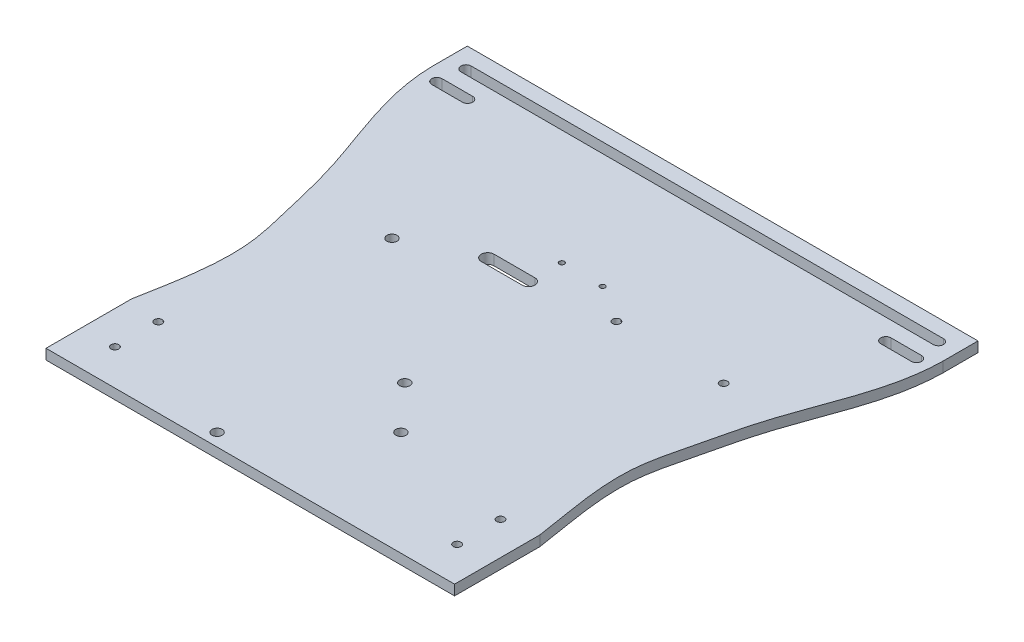
SolidWorks part; units mm, degrees
ref_plane "Front Plane" through (0, 0, 0) normal (0, 0, 1) x (1, 0, 0)
ref_plane "Top Plane" through (0, 0, 0) normal (0, 1, 0) x (1, 0, 0)
ref_plane "Right Plane" through (0, 0, 0) normal (1, 0, 0) x (0, 0, -1)
sketch "Esquisse1" plane through (0, 0, 0) normal (0, 1, 0) x (1, 0, 0)
  line L4 (20.099, -176.7531) -> (180.099, -176.7531)
  line L11 (180.099, -143.3042) -> (180.099, -176.7531)
  line L24 (20.099, -143.3042) -> (20.099, -176.7531)
  line L26 (7.599, 0.2469) -> (192.599, 0.2469) construction
  line L27 (7.599, 2.2469) -> (192.599, 2.2469)
  line L28 (7.599, -1.7531) -> (192.599, -1.7531)
  line L35 (200.099, 8.2469) -> (0.099, 8.2469)
  line L36 (-12.479, 15.7469) -> (206.8188, 15.7469) construction
  line L37 (182, -9.7531) -> (194, -9.7531) construction
  line L38 (182, -7.7531) -> (194, -7.7531)
  line L39 (182, -11.7531) -> (194, -11.7531)
  line L40 (18.198, -9.7531) -> (6.198, -9.7531) construction
  line L41 (18.198, -7.7531) -> (6.198, -7.7531)
  line L42 (18.198, -11.7531) -> (6.198, -11.7531)
  line L45 (0.099, -5.4026) -> (0.099, 8.2469)
  line L46 (75.9115, -59.5989) -> (91.9115, -59.5989) construction
  line L59 (75.9115, -57.0989) -> (91.9115, -57.0989)
  line L60 (75.9115, -62.0989) -> (91.9115, -62.0989)
  line L61 (200.099, -5.4026) -> (200.099, 8.2469)
  circle A1 centre (33.099, -145.7531) radius 1.5
  circle A2 centre (33.099, -162.7531) radius 1.5
  circle A4 centre (167.099, -162.7531) radius 1.5
  circle A5 centre (167.099, -145.7531) radius 1.5
  arc A11 (7.599, 2.2469) -> (7.599, -1.7531) centre (7.599, 0.2469) ccw
  arc A18 (192.599, -1.7531) -> (192.599, 2.2469) centre (192.599, 0.2469) ccw
  circle A21 centre (92.099, -46.7531) radius 1
  circle A22 centre (108.099, -46.7531) radius 1
  arc A23 (182, -7.7531) -> (182, -11.7531) centre (182, -9.7531) ccw
  arc A24 (194, -11.7531) -> (194, -7.7531) centre (194, -9.7531) ccw
  arc A25 (18.198, -7.7531) -> (18.198, -11.7531) centre (18.198, -9.7531) cw
  arc A26 (6.198, -11.7531) -> (6.198, -7.7531) centre (6.198, -9.7531) cw
  circle A27 centre (82.099, -171.7531) radius 2
  circle A28 centre (118.099, -135.7531) radius 2
  arc A29 (75.9115, -57.0989) -> (75.9115, -62.0989) centre (75.9115, -59.5989) ccw
  arc A30 (91.9115, -62.0989) -> (91.9115, -57.0989) centre (91.9115, -59.5989) ccw
  circle A31 centre (164.6774, -55.9468) radius 1.5
  circle A32 centre (122.6774, -55.9468) radius 1.5
  circle A33 centre (50.5454, -71.7018) radius 2
  circle A34 centre (102.0454, -118.2018) radius 2
  spline S0 degree 3 poles (0.099, -5.4026) (0.1707, -10.8635) (2.9271, -30.0947) (14.0836, -54.9544) (20.1927, -81.6516) (26.9733, -108.5697) (22.6238, -129.3491) (20.099, -143.3042) knots 0.011658 0.011658 0.011658 0.011658 0.124408 0.42011 0.574806 0.697903 1 1 1 1
  spline S1 degree 3 poles (200.099, -5.4026) (200.0273, -10.8635) (197.5838, -30.0947) (186.0725, -54.9544) (180.3703, -81.6516) (173.1338, -108.5697) (178.0972, -129.3491) (180.099, -143.3042) knots 0.011658 0.011658 0.011658 0.011658 0.124408 0.42011 0.574806 0.697903 1 1 1 1
  point P0 (0, 0)
  point P18 (100.099, 0.2469)
  point P35 (188, -9.7531)
  point P54 (12.198, -9.7531)
  point P78 (83.9115, -59.5989)
  dimension "D6" = 2
  dimension "D17" = 15
  dimension "D18" = 3
  dimension "D8" = 13
  dimension "D30" = 4
  dimension "D34" = 4
  dimension "D49" = 3
  dimension "D40" = 4
  dimension "D45" = 4
  dimension "D3" = 13
  dimension "D4" = 14
  dimension "D5" = 17
  dimension "D7" = 16
  dimension "D9" = 17
  dimension "D10" = 4
  dimension "D11" = 10
  dimension "D12" = 12
  dimension "D13" = 134
  dimension "D14" = 185
  dimension "D19" = 4
  dimension "D20" = 185
  dimension "D21" = 6
  dimension "D22" = 47
  dimension "D23" = 47
  dimension "D24" = 200
  dimension "D29" = 5
  dimension "D35" = 10
  dimension "D43" = 5
  dimension "D44" = 16
extrude "Boss.-Extru.1" add sketch "Esquisse1" along normal blind 4
